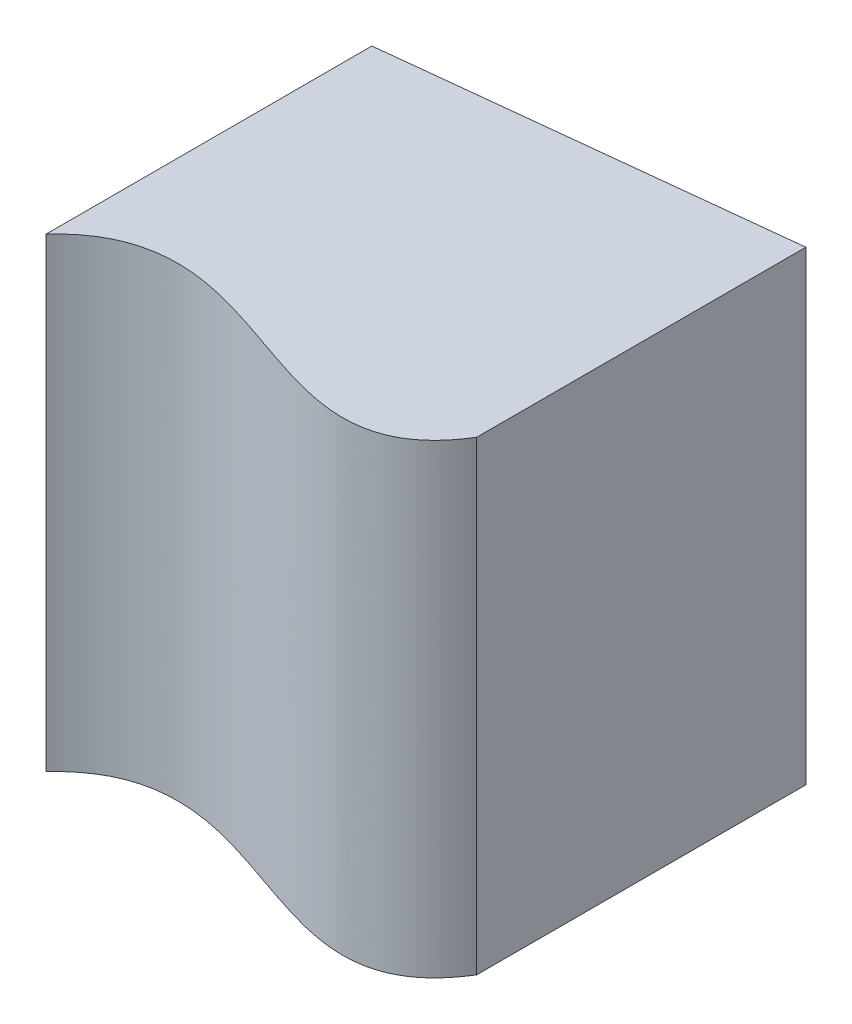
SolidWorks part; units mm, degrees
ref_plane "前视基准面" through (0, 0, 0) normal (0, 0, 1) x (1, 0, 0)
ref_plane "上视基准面" through (0, 0, 0) normal (0, 1, 0) x (1, 0, 0)
ref_plane "右视基准面" through (0, 0, 0) normal (1, 0, 0) x (0, 0, -1)
other "Configuration Table"
sketch "草图1" plane through (0, 0, 0) normal (0, 1, 0) x (1, 0, 0)
  line L0 (-76.8379, -58.8169) -> (-76.8379, 125.1994)
  line L1 (-76.8379, 125.1994) -> (144.1667, 149.3454)
  line L2 (144.1667, 149.3454) -> (144.1667, -36.5972)
  spline S0 degree 3 poles (-76.8379, -58.8169) (-9.5417, 14.7823) (93.3591, -119.9869) (144.1667, -36.5972) knots 0 0 0 0 1 1 1 1
  point P6 (-76.8379, 125.1994)
extrude "凸台-拉伸1" add sketch "草图1" along normal mid plane 263
sketch3d "3D草图1"
  spline S0 degree 1 poles (-76.8379, 2131.4946, 58.8169) (-76.8379, -2131.4847, 58.8169) knots -7.604542 -7.604542 8.604505 8.604505 only from (-76.8379, 131.5, 58.8169) to (-76.8379, -131.5, 58.8169) construction
  spline S1 degree 1 poles (-76.8379, 131.5, 58.8169) (-76.8379, -131.5, 58.8169) knots 0 0 1 1
sketch3d "3D草图2"
  spline S0 degree 1 poles (-21.0602, 2131.4946, 36.0221) (-21.0602, -2131.4847, 36.0221) knots -7.604542 -7.604542 8.604505 8.604505 only from (-21.0602, 131.5, 36.0221) to (-21.0602, -131.5, 36.0221) construction
  spline S1 degree 1 poles (-21.0602, 131.5, 36.0221) (-21.0602, -131.5, 36.0221) knots 0 0 1 1
sketch3d "3D草图3"
  spline S0 degree 1 poles (39.8476, 2131.4946, 51.3785) (39.8476, -2131.4847, 51.3785) knots -7.604542 -7.604542 8.604505 8.604505 only from (39.8476, 131.5, 51.3785) to (39.8476, -131.5, 51.3785) construction
  spline S1 degree 1 poles (39.8476, 131.5, 51.3785) (39.8476, -131.5, 51.3785) knots 0 0 1 1
sketch3d "3D草图4"
  spline S0 degree 1 poles (97.6638, 2131.4946, 64.8992) (97.6638, -2131.4847, 64.8992) knots -7.604542 -7.604542 8.604505 8.604505 only from (97.6638, 131.5, 64.8992) to (97.6638, -131.5, 64.8992) construction
  spline S1 degree 1 poles (97.6638, 131.5, 64.8992) (97.6638, -131.5, 64.8992) knots 0 0 1 1
sketch3d "3D草图5"
  spline S0 degree 1 poles (144.1667, 2131.4946, 36.5972) (144.1667, -2131.4847, 36.5972) knots -7.604542 -7.604542 8.604505 8.604505 only from (144.1667, 131.5, 36.5972) to (144.1667, -131.5, 36.5972) construction
  spline S1 degree 1 poles (144.1667, 131.5, 36.5972) (144.1667, -131.5, 36.5972) knots 0 0 1 1
sketch3d "3D草图6"
  spline S0 degree 3 poles (-2.5166, 131.5, 2052.5041) (-522.1906, 131.5, -2144.7126) (638.7133, 131.5, 2245.2569) (-50.7991, 131.5, -1950.9388) knots -1.225297 -1.225297 -1.225297 -1.225297 2.202139 2.202139 2.202139 2.202139 only from (-76.8379, 131.5, 58.8169) to (144.1667, 131.5, 36.5972) construction
  spline S1 degree 3 poles (-76.8379, 131.5, 58.8169) (-9.5417, 131.5, -14.7823) (93.3591, 131.5, 119.9869) (144.1667, 131.5, 36.5972) knots 0 0 0 0 1 1 1 1
sketch3d "3D草图7"
  spline S0 degree 3 poles (-2.5166, 65.75, 2052.5041) (-522.1906, 65.75, -2144.7126) (638.7133, 65.75, 2245.2569) (-50.7991, 65.75, -1950.9388) knots -1.225297 -1.225297 -1.225297 -1.225297 2.202139 2.202139 2.202139 2.202139 only from (-76.8379, 65.75, 58.8169) to (144.1667, 65.75, 36.5972) construction
  spline S1 degree 3 poles (-76.8379, 65.75, 58.8169) (-9.5417, 65.75, -14.7823) (93.3591, 65.75, 119.9869) (144.1667, 65.75, 36.5972) knots 0 0 0 0 1 1 1 1
sketch3d "3D草图8"
  spline S0 degree 3 poles (-2.5166, 0, 2052.5041) (-522.1906, 0, -2144.7126) (638.7133, 0, 2245.2569) (-50.7991, 0, -1950.9388) knots -1.225297 -1.225297 -1.225297 -1.225297 2.202139 2.202139 2.202139 2.202139 only from (-76.8379, 0, 58.8169) to (144.1667, 0, 36.5972) construction
  spline S1 degree 3 poles (-76.8379, 0, 58.8169) (-9.5417, 0, -14.7823) (93.3591, 0, 119.9869) (144.1667, 0, 36.5972) knots 0 0 0 0 1 1 1 1
sketch3d "3D草图9"
  spline S0 degree 3 poles (-2.5166, -65.75, 2052.5041) (-522.1906, -65.75, -2144.7126) (638.7133, -65.75, 2245.2569) (-50.7991, -65.75, -1950.9388) knots -1.225297 -1.225297 -1.225297 -1.225297 2.202139 2.202139 2.202139 2.202139 only from (-76.8379, -65.75, 58.8169) to (144.1667, -65.75, 36.5972) construction
  spline S1 degree 3 poles (-76.8379, -65.75, 58.8169) (-9.5417, -65.75, -14.7823) (93.3591, -65.75, 119.9869) (144.1667, -65.75, 36.5972) knots 0 0 0 0 1 1 1 1
sketch3d "3D草图10"
  spline S0 degree 3 poles (-2.5166, -131.5, 2052.5041) (-522.1906, -131.5, -2144.7126) (638.7133, -131.5, 2245.2569) (-50.7991, -131.5, -1950.9388) knots -1.225297 -1.225297 -1.225297 -1.225297 2.202139 2.202139 2.202139 2.202139 only from (-76.8379, -131.5, 58.8169) to (144.1667, -131.5, 36.5972) construction
  spline S1 degree 3 poles (-76.8379, -131.5, 58.8169) (-9.5417, -131.5, -14.7823) (93.3591, -131.5, 119.9869) (144.1667, -131.5, 36.5972) knots 0 0 0 0 1 1 1 1
sketch3d "3D草图11"
  spline S0 degree 1 poles (-76.8379, -2131.4946, -125.1994) (-76.8379, 2131.4847, -125.1994) knots -7.604542 -7.604542 8.604505 8.604505 only from (-76.8379, -131.5, -125.1994) to (-76.8379, 131.5, -125.1994) construction
  spline S1 degree 1 poles (-76.8379, -131.5, -125.1994) (-76.8379, 131.5, -125.1994) knots 0 0 1 1
sketch3d "3D草图12"
  spline S0 degree 1 poles (-21.5868, -2131.4946, -131.2359) (-21.5868, 2131.4847, -131.2359) knots -7.604542 -7.604542 8.604505 8.604505 only from (-21.5868, -131.5, -131.2359) to (-21.5868, 131.5, -131.2359) construction
  spline S1 degree 1 poles (-21.5868, -131.5, -131.2359) (-21.5868, 131.5, -131.2359) knots 0 0 1 1
sketch3d "3D草图13"
  spline S0 degree 1 poles (33.6644, -2131.4946, -137.2724) (33.6644, 2131.4847, -137.2724) knots -7.604542 -7.604542 8.604505 8.604505 only from (33.6644, -131.5, -137.2724) to (33.6644, 131.5, -137.2724) construction
  spline S1 degree 1 poles (33.6644, -131.5, -137.2724) (33.6644, 131.5, -137.2724) knots 0 0 1 1
sketch3d "3D草图14"
  spline S0 degree 1 poles (88.9155, -2131.4946, -143.3089) (88.9155, 2131.4847, -143.3089) knots -7.604542 -7.604542 8.604505 8.604505 only from (88.9155, -131.5, -143.3089) to (88.9155, 131.5, -143.3089) construction
  spline S1 degree 1 poles (88.9155, -131.5, -143.3089) (88.9155, 131.5, -143.3089) knots 0 0 1 1
sketch3d "3D草图15"
  spline S0 degree 1 poles (144.1667, -2131.4946, -149.3454) (144.1667, 2131.4847, -149.3454) knots -7.604542 -7.604542 8.604505 8.604505 only from (144.1667, -131.5, -149.3454) to (144.1667, 131.5, -149.3454) construction
  spline S1 degree 1 poles (144.1667, -131.5, -149.3454) (144.1667, 131.5, -149.3454) knots 0 0 1 1
sketch3d "3D草图16"
  spline S0 degree 1 poles (-2064.9995, -131.5, 92.0185) (2132.3254, -131.5, -366.563) knots -8.996019 -8.996019 9.996006 9.996006 only from (-76.8379, -131.5, -125.1994) to (144.1667, -131.5, -149.3454) construction
  spline S1 degree 1 poles (-76.8379, -131.5, -125.1994) (144.1667, -131.5, -149.3454) knots 0 0 1 1
sketch3d "3D草图17"
  spline S0 degree 1 poles (-2064.9995, -65.75, 92.0185) (2132.3254, -65.75, -366.563) knots -8.996019 -8.996019 9.996006 9.996006 only from (-76.8379, -65.75, -125.1994) to (144.1667, -65.75, -149.3454) construction
  spline S1 degree 1 poles (-76.8379, -65.75, -125.1994) (144.1667, -65.75, -149.3454) knots 0 0 1 1
sketch3d "3D草图18"
  spline S0 degree 1 poles (-2064.9995, 0, 92.0185) (2132.3254, 0, -366.563) knots -8.996019 -8.996019 9.996006 9.996006 only from (-76.8379, 0, -125.1994) to (144.1667, 0, -149.3454) construction
  spline S1 degree 1 poles (-76.8379, 0, -125.1994) (144.1667, 0, -149.3454) knots 0 0 1 1
sketch3d "3D草图19"
  spline S0 degree 1 poles (-2064.9995, 65.75, 92.0185) (2132.3254, 65.75, -366.563) knots -8.996019 -8.996019 9.996006 9.996006 only from (-76.8379, 65.75, -125.1994) to (144.1667, 65.75, -149.3454) construction
  spline S1 degree 1 poles (-76.8379, 65.75, -125.1994) (144.1667, 65.75, -149.3454) knots 0 0 1 1
sketch3d "3D草图20"
  spline S0 degree 1 poles (-2064.9995, 131.5, 92.0185) (2132.3254, 131.5, -366.563) knots -8.996019 -8.996019 9.996006 9.996006 only from (-76.8379, 131.5, -125.1994) to (144.1667, 131.5, -149.3454) construction
  spline S1 degree 1 poles (-76.8379, 131.5, -125.1994) (144.1667, 131.5, -149.3454) knots 0 0 1 1
